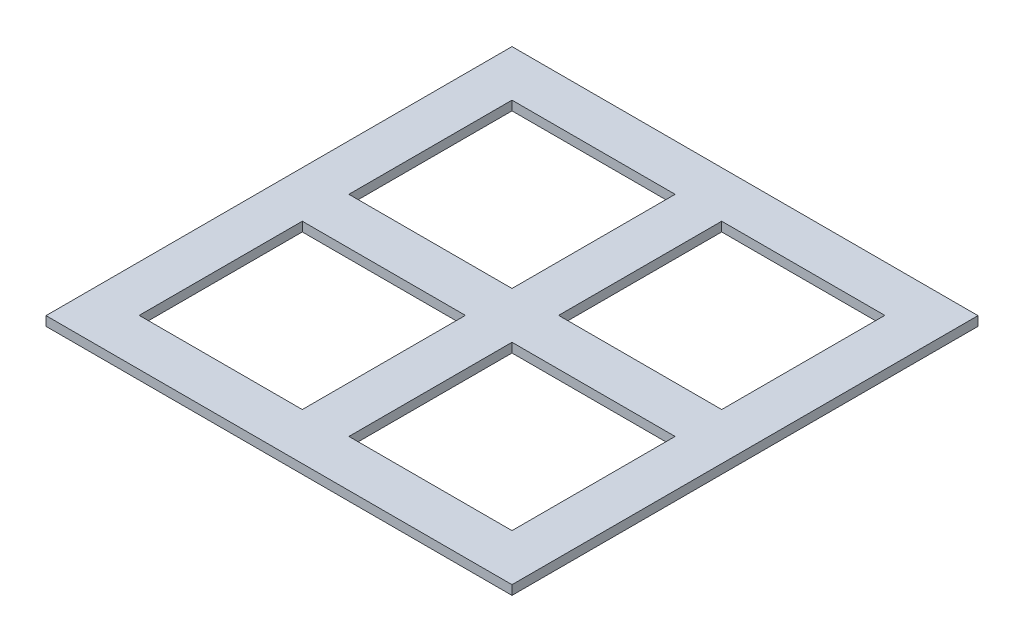
SolidWorks part; units mm, degrees
ref_plane "Front Plane" through (0, 0, 0) normal (0, 0, 1) x (1, 0, 0)
ref_plane "Top Plane" through (0, 0, 0) normal (0, 1, 0) x (1, 0, 0)
ref_plane "Right Plane" through (0, 0, 0) normal (1, 0, 0) x (0, 0, -1)
sketch "Sketch1" plane through (0, 0, 0) normal (0, 1, 0) x (1, 0, 0)
  line L0 (9.9531, 45.0469) -> (9.9531, 10.0469)
  line L1 (0, 0) -> (100, 0)
  line L2 (0, 0) -> (0, 100)
  line L3 (0, 100) -> (100, 100)
  line L4 (100, 0) -> (100, 100)
  line L5 (-104.3528, -56.8982) -> (10.8602, -56.8982)
  line L6 (-104.3528, -56.8982) -> (-104.3528, -33.7612)
  line L8 (148.2257, 61.5592) -> (158.2257, 61.5592) construction
  line L9 (0, 100) -> (0, 90.0469)
  line L10 (44.9531, 90.0469) -> (9.9531, 90.0469)
  line L11 (9.9531, 90.0469) -> (9.9531, 55.0469)
  line L12 (9.9531, 10.0469) -> (44.9531, 10.0469)
  line L13 (89.9531, 10.0469) -> (89.9531, 45.0469)
  line L14 (89.9531, 90.0469) -> (54.9531, 90.0469)
  line L16 (44.9531, 55.0469) -> (9.9531, 55.0469)
  line L17 (89.9531, 55.0469) -> (54.9531, 55.0469)
  line L18 (89.9531, 45.0469) -> (54.9531, 45.0469)
  line L19 (44.9531, 90.0469) -> (44.9531, 55.0469)
  line L20 (54.9531, 90.0469) -> (54.9531, 55.0469)
  line L21 (89.9531, 55.0469) -> (89.9531, 90.0469)
  line L23 (54.9531, 45.0469) -> (54.9531, 10.0469)
  line L25 (54.9531, 45.0469) -> (100, 0) construction
  line L28 (44.9531, 45.0469) -> (44.9531, 10.0469)
  line L30 (44.9531, 45.0469) -> (9.9531, 45.0469)
  line L32 (54.9531, 10.0469) -> (89.9531, 10.0469)
extrude "Boss-Extrude1" add sketch "Sketch1" along normal blind 2 contours L1 L4 L3 L2 L32 L23 L18 L13 L30 L28 L12 L0 L21 L17 L20 L14 L10 L19 L16 L11
